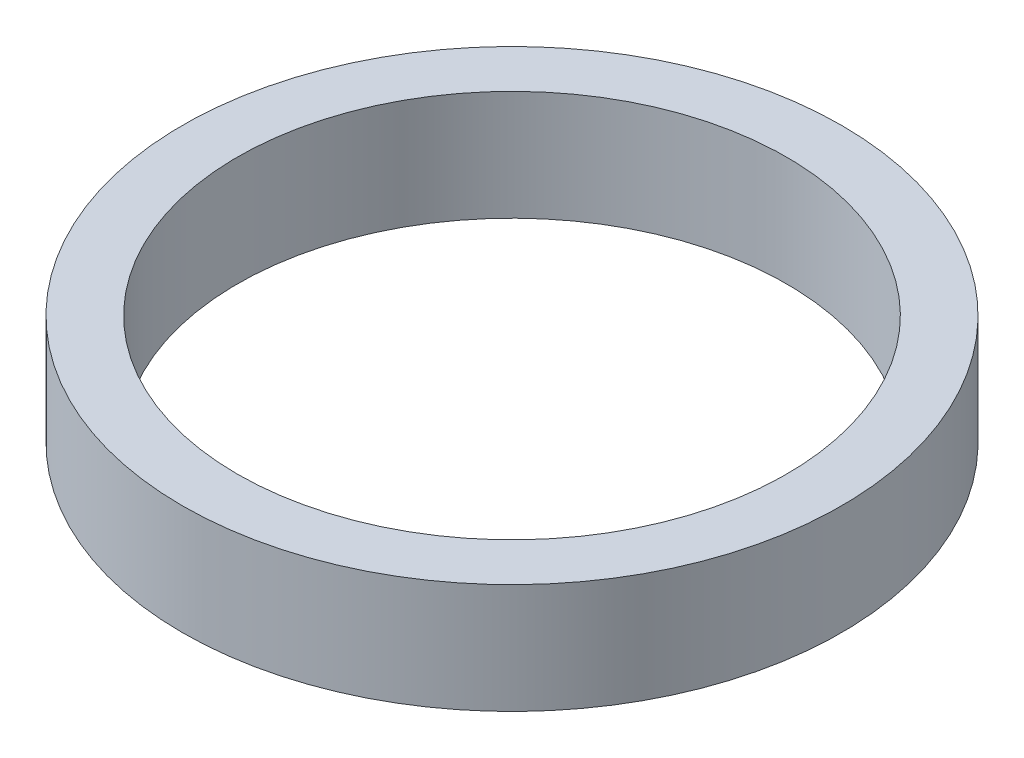
SolidWorks part; units mm, degrees
ref_plane "Front Plane" through (0, 0, 0) normal (0, 0, 1) x (1, 0, 0)
ref_plane "Top Plane" through (0, 0, 0) normal (0, 1, 0) x (1, 0, 0)
ref_plane "Right Plane" through (0, 0, 0) normal (1, 0, 0) x (0, 0, -1)
sketch "Sketch2" plane through (0, 0, 0) normal (0, 1, 0) x (1, 0, 0)
  circle A0 centre (0, 0) radius 15
  circle A1 centre (0, 0) radius 12.5
  dimension "D1" = 30
  dimension "D2" = 25
extrude "Boss-Extrude1" add sketch "Sketch2" along normal blind 5
